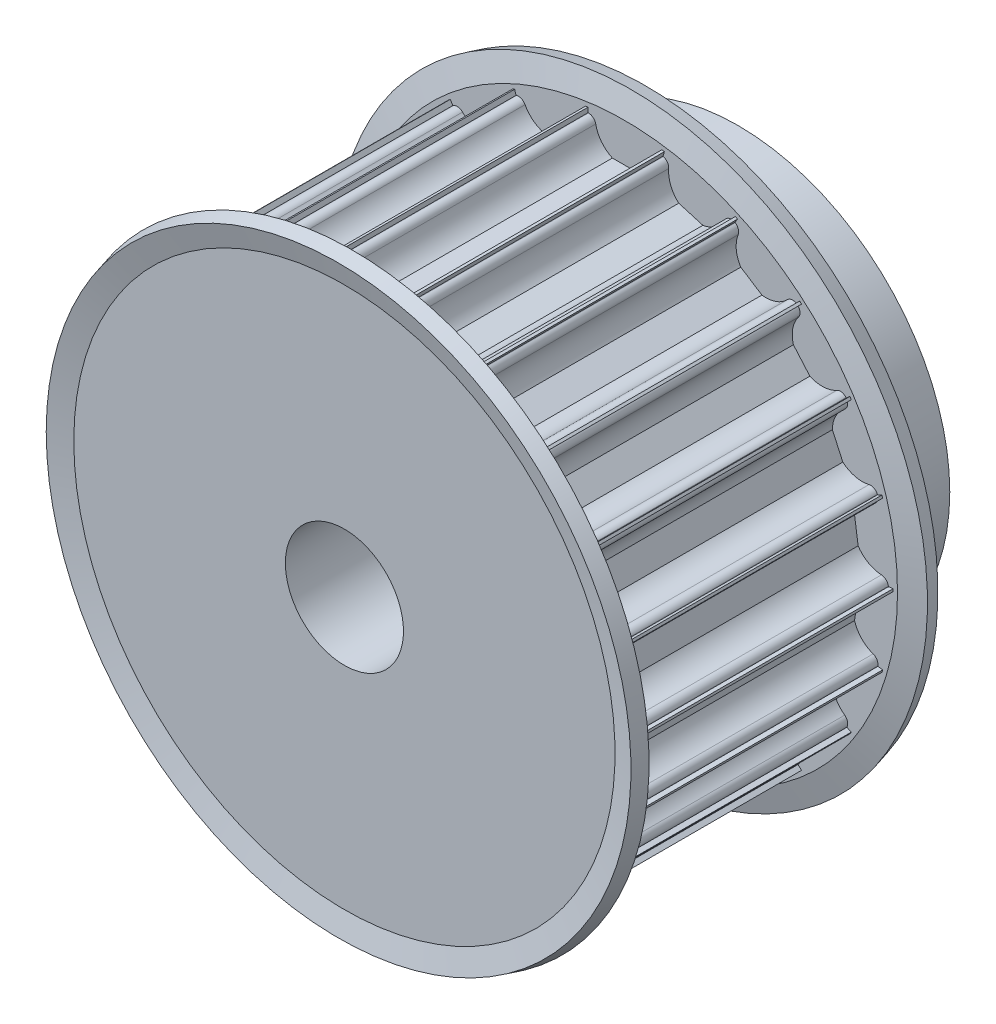
SolidWorks part; units mm, degrees
ref_plane "Front Plane" through (0, 0, 0) normal (0, 0, 1) x (1, 0, 0)
ref_plane "Top Plane" through (0, 0, 0) normal (0, 1, 0) x (1, 0, 0)
ref_plane "Right Plane" through (0, 0, 0) normal (1, 0, 0) x (0, 0, -1)
ref_axis "Axis1" through (0, 0, -88.99) along (0, 0, 1)
sketch "Sketch1" plane through (0, 0, 0) normal (1, 0, 0) x (0, 0, -1)
  line L0 (0, 6) -> (0, 27.25)
  line L1 (0, 27.25) -> (30, 27.25)
  line L2 (30, 27.25) -> (30, 21.5)
  line L3 (30, 21.5) -> (40, 21.5)
  line L4 (40, 21.5) -> (40, 6)
  line L5 (40, 6) -> (0, 6)
  line L6 (88.99, 0) -> (-88.99, 0) construction
  dimension "D1" = 30
  dimension "D2" = 21.25
  dimension "D3" = 10
  dimension "D4" = 15.5
  dimension "D5" = 6
revolve "Revolve1" add sketch "Sketch1" angle 360 about axis through (0, 0, -88.99) along (0, 0, 1)
sketch "Sketch2" plane through (0, 0, 0) normal (0, 0, 1) x (1, 0, 0)
  line L0 (3.7071, 26.5) -> (3.75, 26.5)
  line L1 (-3.75, 28.5) -> (3.75, 28.5)
  line L2 (-3.75, 28.5) -> (-3.75, 26.5)
  line L3 (-3.75, 26.5) -> (-3.7071, 26.5)
  line L4 (3.75, 28.5) -> (3.75, 26.5)
  line L5 (-3.75, 28.5) -> (3.75, 26.5) construction
  line L6 (-3.75, 26.5) -> (3.75, 28.5) construction
  line L7 (1.2774, 23.75) -> (-1.2774, 23.75)
  arc A1 (-2.972, 25.8987) -> (-1.2774, 23.75) centre (0, 26.5) ccw
  arc A2 (-2.972, 25.8987) -> (-3.7071, 26.5) centre (-3.7071, 25.75) ccw
  arc A3 (2.972, 25.8987) -> (3.7071, 26.5) centre (3.7071, 25.75) cw
  arc A4 (1.2774, 23.75) -> (2.972, 25.8987) centre (0, 26.5) ccw
  point P3 (0, 27.5)
  point P15 (3.0322, 26.5)
  dimension "D3" = 26.5
  dimension "D5" = 0.75
  dimension "D4" = 0.75
  dimension "D1" = 2
  dimension "D2" = 7.5
  dimension "D6" = 2.75
extrude "Cut-Extrude1" cut sketch "Sketch2" against normal blind 48
pattern_circular "CirPattern1" count 22 over 360 about axis through (0, 0, 0) along (0, 0, 1) of "Cut-Extrude1"
sketch "Sketch3" plane through (0, 0, 0) normal (1, 0, 0) x (0, 0, -1)
  line L0 (1.5, 27.6907) -> (0.0511, 27.3025) construction
  line L1 (0, 27.6907) -> (1.5, 27.6907)
  line L2 (0, 27.6907) -> (0, 22.6907)
  line L3 (0, 22.6907) -> (1.5, 22.6907)
  line L4 (1.5, 27.6907) -> (1.5, 22.6907)
  line L5 (1.5, 27.6907) -> (0.8569, 30.0907)
  line L6 (0.0511, 27.3025) -> (-0.592, 29.7025)
  line L7 (0.8569, 30.0907) -> (-0.592, 29.7025)
  line L8 (0, 25.687) -> (0, 23.1478) construction
  line L9 (0, 26.9907) -> (30, 26.9907) construction
  line L10 (15, 26.9539) -> (15, -26.9907) construction
  line L11 (30, 26.9539) -> (0, 26.9539) construction
  line L12 (30, -26.9907) -> (0, -26.9907) construction
  line L13 (28.5, 27.6907) -> (29.9489, 27.3025) construction
  line L14 (29.1431, 30.0907) -> (30.592, 29.7025)
  line L15 (29.9489, 27.3025) -> (30.592, 29.7025)
  line L16 (28.5, 27.6907) -> (29.1431, 30.0907)
  line L17 (28.5, 27.6907) -> (28.5, 22.6907)
  line L18 (30, 22.6907) -> (28.5, 22.6907)
  line L19 (30, 27.6907) -> (30, 22.6907)
  line L20 (30, 27.6907) -> (28.5, 27.6907)
  dimension "D1" = 1.5
  dimension "D2" = 5
  dimension "D3" = 1.5
  dimension "D4" = 165
  dimension "D5" = 2.4
  dimension "D6" = 0.7
revolve "Revolve2" add sketch "Sketch3" angle 360 about axis through (0, 0, -88.99) along (0, 0, 1)
